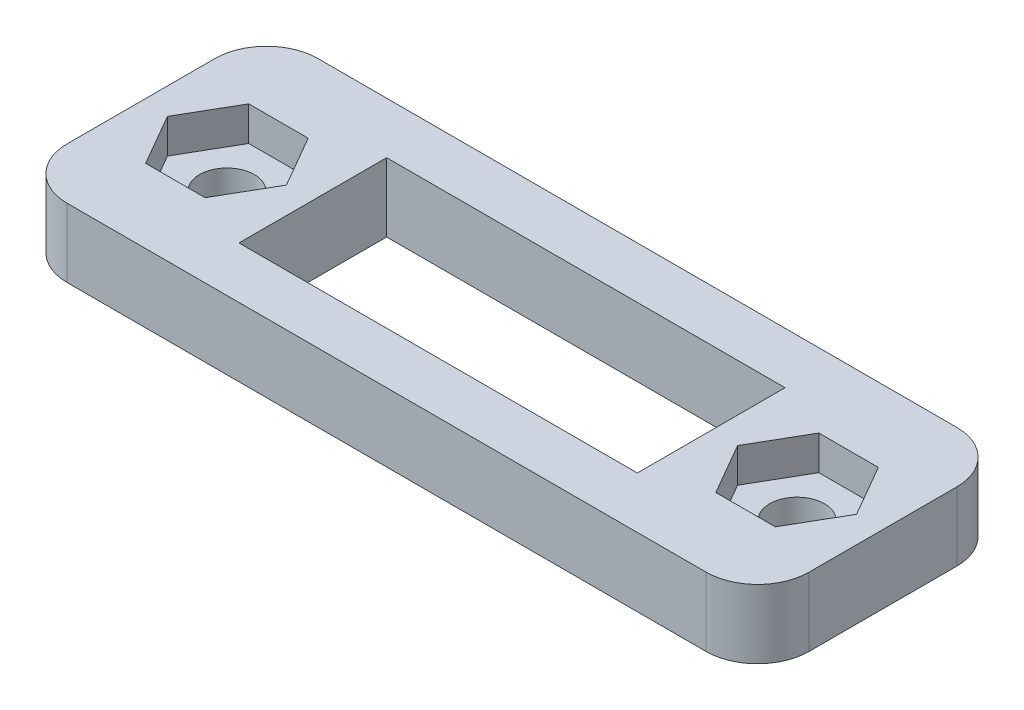
SolidWorks part; units mm, degrees
ref_plane "Front Plane" through (0, 0, 0) normal (0, 0, 1) x (1, 0, 0)
ref_plane "Top Plane" through (0, 0, 0) normal (0, 1, 0) x (1, 0, 0)
ref_plane "Right Plane" through (0, 0, 0) normal (1, 0, 0) x (0, 0, -1)
sketch "Sketch1" plane through (0, 0, 0) normal (0, 1, 0) x (1, 0, 0)
  line L1 (-11.6, 4.3) -> (11.6, 4.3)
  line L2 (-11.6, 4.3) -> (-11.6, -4.3)
  line L3 (-11.6, -4.3) -> (11.6, -4.3)
  line L4 (11.6, 4.3) -> (11.6, -4.3)
  line L9 (-21.6, 7.3) -> (21.6, 7.3)
  line L10 (-21.6, 7.3) -> (-21.6, -7.3)
  line L11 (-21.6, -7.3) -> (21.6, -7.3)
  line L12 (21.6, 7.3) -> (21.6, -7.3)
  point P4 (0, 4.3)
  point P6 (-11.6, 0)
  point P11 (0, 7.3)
  point P12 (-21.6, 0)
  point P17 (0, 0)
  dimension "D1" = 23.2
  dimension "D2" = 8.6
  dimension "D3" = 3
  dimension "D4" = 10
extrude "Boss-Extrude1" add sketch "Sketch1" along normal blind 4
sketch "Sketch4" plane through (0, 4, 0) normal (0, 1, 0) x (1, 0, 0)
  line L0 (21.6, -7.3) -> (21.6, 7.3) construction
  line L1 (18.3321, -3) -> (20.0641, 0)
  line L2 (20.0641, 0) -> (18.3321, 3)
  line L3 (18.3321, 3) -> (14.8679, 3)
  line L4 (14.8679, 3) -> (13.1359, 0)
  line L5 (13.1359, 0) -> (14.8679, -3)
  line L6 (14.8679, -3) -> (18.3321, -3)
  line L7 (0, 7.3) -> (0, -7.3) construction
  line L8 (21.6, 7.3) -> (-21.6, 7.3) construction
  line L9 (-21.6, -7.3) -> (21.6, -7.3) construction
  line L10 (-14.8679, -3) -> (-18.3321, -3)
  line L11 (-13.1359, 0) -> (-14.8679, -3)
  line L12 (-14.8679, 3) -> (-13.1359, 0)
  line L13 (-18.3321, 3) -> (-14.8679, 3)
  line L14 (-20.0641, 0) -> (-18.3321, 3)
  line L15 (-18.3321, -3) -> (-20.0641, 0)
  circle A0 centre (16.6, 0) radius 3 construction
  dimension "D1" = 5
  dimension "D2" = 6
extrude "Cut-Extrude1" cut sketch "Sketch4" against normal blind 2
sketch "Sketch5" plane through (0, 2, 0) normal (0, 1, 0) x (1, 0, 0)
  line L0 (0, 4.3) -> (0, -4.3) construction
  line L1 (11.6, 4.3) -> (-11.6, 4.3) construction
  line L2 (-11.6, -4.3) -> (11.6, -4.3) construction
  line L3 (-21.6, 7.3) -> (-21.6, -7.3) construction
  circle A0 centre (-16.6, 0) radius 1.6
  circle A1 centre (16.6, 0) radius 1.6
  point P8 (0, 0)
  dimension "D1" = 3.2
  dimension "D2" = 5
extrude "Cut-Extrude2" cut sketch "Sketch5" against normal through all
fillet "Fillet2" radius 3 4 edges at (21.6, 2, -7.3) (-21.6, 2, -7.3) (-21.6, 2, 7.3) (21.6, 2, 7.3)
